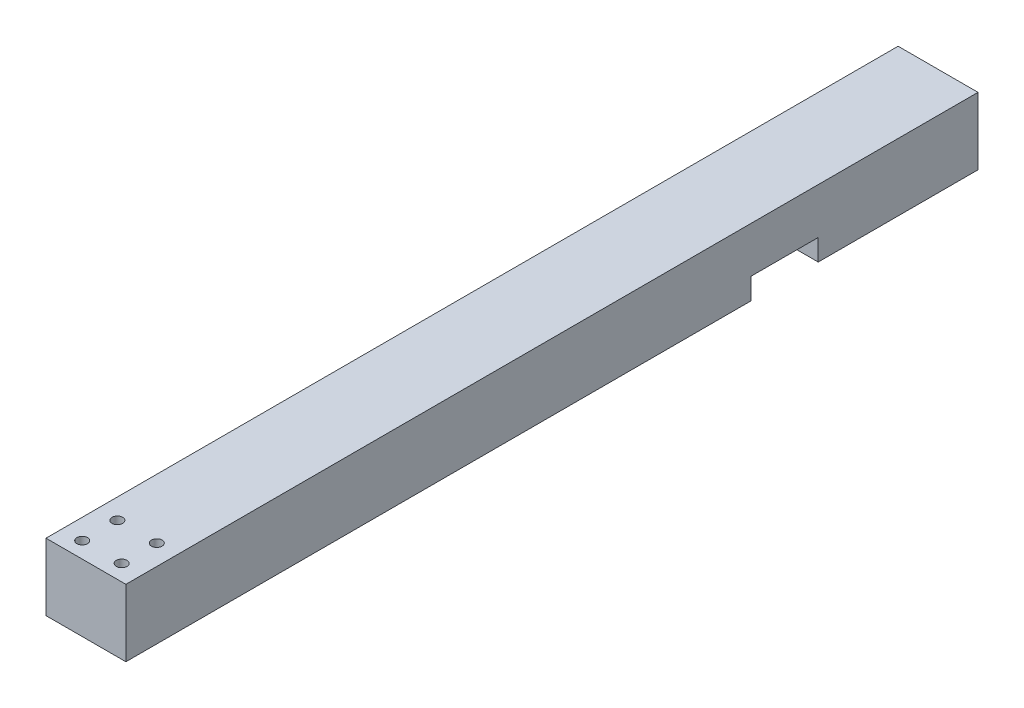
SolidWorks part; units mm, degrees
ref_plane "Front" through (0, 0, 0) normal (0, 0, 1) x (1, 0, 0)
ref_plane "Top" through (0, 0, 0) normal (0, 1, 0) x (1, 0, 0)
ref_plane "Right" through (0, 0, 0) normal (1, 0, 0) x (0, 0, -1)
sketch "Esquisse1" plane through (0, 0, 0) normal (0, 0, 1) x (1, 0, 0)
  line L1 (0, 0) -> (75, 0)
  line L2 (0, 0) -> (0, 63)
  line L3 (0, 63) -> (75, 63)
  line L4 (75, 0) -> (75, 63)
  dimension "D1" = 63
  dimension "D2" = 75
extrude "Boss.-Extru.1" add sketch "Esquisse1" along normal blind 800
sketch "Esquisse2" plane through (0, 0, 0) normal (0, -1, 0) x (1, 0, 0)
  line L0 (19, 800) -> (19, 752) construction
  line L1 (0, 800) -> (75, 800) construction
  line L2 (0, 800) -> (0, 0) construction
  line L3 (37.5, 800) -> (37.5, 937.2696) construction
  circle A0 centre (19, 752) radius 5
  circle A1 centre (19, 785) radius 5
  circle A2 centre (56, 785) radius 5
  circle A3 centre (56, 752) radius 5
  dimension "D1" = 10
  dimension "D2" = 15
  dimension "D4" = 33
  dimension "D3" = 19
extrude "Enlèv. mat.-Extru.1" cut sketch "Esquisse2" against normal through all
sketch "Esquisse3" plane through (0, 0, 0) normal (0, -1, 0) x (1, 0, 0)
  line L0 (0, 800) -> (0, 0) construction
  line L1 (0, 150) -> (75, 150)
  line L2 (0, 150) -> (0, 213)
  line L3 (0, 213) -> (75, 213)
  line L4 (75, 150) -> (75, 213)
  line L5 (75, 800) -> (75, 0) construction
  line L6 (0, 0) -> (75, 0) construction
  dimension "D1" = 63
  dimension "D2" = 150
extrude "Enlèv. mat.-Extru.2" cut sketch "Esquisse3" against normal blind 20
